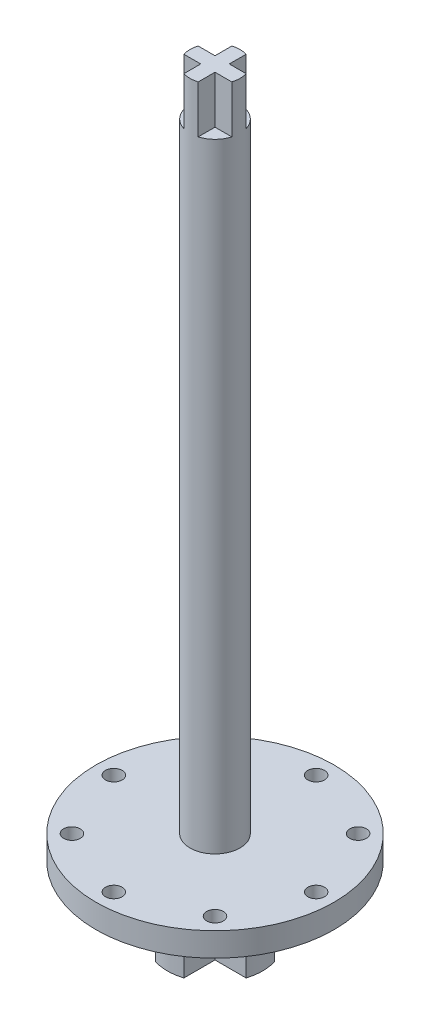
SolidWorks part; units mm, degrees
ref_plane "Front Plane" through (0, 0, 0) normal (0, 0, 1) x (1, 0, 0)
ref_plane "Top Plane" through (0, 0, 0) normal (0, 1, 0) x (1, 0, 0)
ref_plane "Right Plane" through (0, 0, 0) normal (1, 0, 0) x (0, 0, -1)
sketch "Sketch1" plane through (0, 0, 0) normal (1, 0, 0) x (0, 0, -1)
  line L0 (0, 49.9145) -> (0, -47.1795) construction
  line L1 (-5.25, 80) -> (-5.25, -60)
  line L2 (-5.25, -60) -> (-25, -60)
  line L3 (-25, -60) -> (-25, -65)
  line L4 (-25, -65) -> (-10, -65)
  line L5 (-10, -65) -> (-10, -80)
  line L6 (-5.25, 80) -> (0, 80)
  line L7 (-10, -80) -> (0, -80)
  line L8 (0, 80) -> (0, -80)
  point P5 (0, 0)
  dimension "D1" = 50
  dimension "D2" = 10.5
  dimension "D3" = 5
  dimension "D4" = 160
  dimension "D5" = 10
  dimension "D6" = 5
  dimension "D7" = 15
revolve "Revolve1" add sketch "Sketch1" angle 360 about L0
sketch "Sketch2" plane through (0, -60, 0) normal (0, 1, 0) x (1, 0, 0)
  line L0 (0, 26.2906) -> (0, -26.8777) construction
  line L1 (0, 0) -> (-34.5757, 0) construction
  line L2 (0, 0) -> (-15.026, 15.026) construction
  circle A0 centre (0, -21.25) radius 1.75
  circle A1 centre (-15.026, -15.026) radius 1.75
  circle A2 centre (-21.25, 0) radius 1.75
  circle A3 centre (-15.026, 15.026) radius 1.75
  circle A4 centre (0, 21.25) radius 1.75
  circle A5 centre (15.026, 15.026) radius 1.75
  circle A6 centre (21.25, 0) radius 1.75
  circle A7 centre (15.026, -15.026) radius 1.75
  circle A8 centre (0, 0) radius 21.25 construction
  circle A9 centre (0, 0) radius 25 construction
  dimension "D1" = 42.5
  dimension "D3" = 3.5
  dimension "D2" = 45
extrude "Cut-Extrude1" cut sketch "Sketch2" against normal blind 10
sketch "Sketch3" plane through (0, -80, 0) normal (0, -1, 0) x (1, 0, 0)
  line L0 (0, 13.2431) -> (0, -12.7865) construction
  line L1 (-14.8088, 0) -> (14.4826, 0) construction
  line L2 (-3, 9.5394) -> (-3, 3)
  line L3 (-3, 3) -> (-9.5394, 3)
  line L4 (-3, -3) -> (-9.5394, -3)
  line L5 (3, -3) -> (9.5394, -3)
  line L6 (3, 3) -> (9.5394, 3)
  line L7 (3, 9.5394) -> (3, 3)
  line L8 (3, -9.5394) -> (3, -3)
  line L9 (-3, -9.5394) -> (-3, -3)
  circle A0 centre (0, 0) radius 10 construction
  arc A1 (-3, 9.5394) -> (-9.5394, 3) centre (0, 0) ccw
  arc A2 (3, 9.5394) -> (9.5394, 3) centre (0, 0) cw
  arc A3 (3, -9.5394) -> (9.5394, -3) centre (0, 0) ccw
  arc A4 (-3, -9.5394) -> (-9.5394, -3) centre (0, 0) cw
  dimension "D1" = 6
  dimension "D3" = 10
  dimension "D2" = 6
extrude "Cut-Extrude2" cut sketch "Sketch3" against normal up to surface (15 mm away) up to face at (0, -65, 19.5)
sketch "Sketch4" plane through (0, 80, 0) normal (0, 1, 0) x (1, 0, 0)
  line L0 (0, 10.6337) -> (0, -11.9384) construction
  line L1 (-10.2422, 0) -> (11.0251, 0) construction
  line L2 (-1.5, 5.0312) -> (-1.5, 1.5)
  line L3 (-1.5, 1.5) -> (-5.0312, 1.5)
  line L4 (5.0312, 1.5) -> (1.5, 1.5)
  line L5 (1.5, 1.5) -> (1.5, 5.0312)
  line L6 (1.5, -5.0312) -> (1.5, -1.5)
  line L7 (1.5, -1.5) -> (5.0312, -1.5)
  line L8 (-5.0312, -1.5) -> (-1.5, -1.5)
  line L9 (-1.5, -1.5) -> (-1.5, -5.0312)
  circle A0 centre (0, 0) radius 5.25 construction
  circle A1 centre (0, 0) radius 5.25 construction
  arc A2 (-5.0312, 1.5) -> (-1.5, 5.0312) centre (0, 0) cw
  arc A3 (1.5, 5.0312) -> (5.0312, 1.5) centre (0, 0) cw
  arc A4 (5.0312, -1.5) -> (1.5, -5.0312) centre (0, 0) cw
  arc A5 (-1.5, -5.0312) -> (-5.0312, -1.5) centre (0, 0) cw
  point P25 (0, 0)
  circle M5 centre (0, 0) radius 5.25
  dimension "D2" = 4
  dimension "D1" = 3
extrude "Cut-Extrude3" cut sketch "Sketch4" against normal blind 10 contours L9 L8 M5 | L7 L6 M5 | L5 L4 M5 | A2 L2 L3
